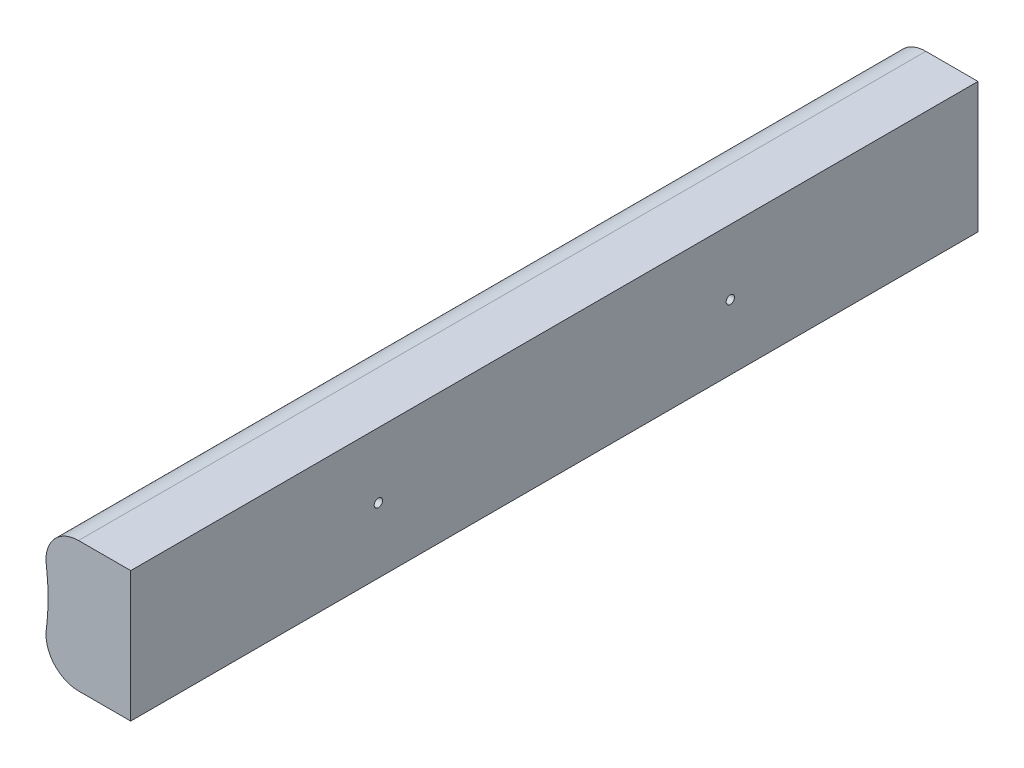
SolidWorks part; units mm, degrees
ref_plane "Front" through (0, 0, 0) normal (0, 0, 1) x (1, 0, 0)
ref_plane "Top" through (0, 0, 0) normal (0, 1, 0) x (1, 0, 0)
ref_plane "Right" through (0, 0, 0) normal (1, 0, 0) x (0, 0, -1)
sketch "Sketch1" plane through (0, 0, 0) normal (0, 0, 1) x (1, 0, 0)
  line L0 (-81.456, -19.8133) -> (-82.3706, -28.3793)
  line L1 (-50.8, -63.5) -> (0, -63.5)
  line L2 (0, -63.5) -> (0, 63.5)
  line L3 (0, 63.5) -> (-50.8, 63.5)
  line L4 (-82.3706, 28.3793) -> (-81.456, 19.8133)
  line L5 (0, 0) -> (-160.6881, 0) construction
  line L6 (-50.8, 96.0303) -> (-50.8, -98.1367) construction
  arc A0 (-82.3706, -28.3793) -> (-50.8, -63.5) centre (-50.8, -31.75) ccw
  arc A1 (-50.8, 63.5) -> (-82.3706, 28.3793) centre (-50.8, 31.75) ccw
  arc A2 (-81.456, -19.8133) -> (-81.456, 19.8133) centre (-267.0315, 0) ccw
  dimension "D2" = 31.75
  dimension "D4" = 186.6302
  dimension "D5" = 50.8
  dimension "D6" = 80.4013
  dimension "D1" = 127
extrude "Extrude1" add sketch "Sketch1" along normal mid plane 825.5
hole_wizard "A (0.234) Diameter Hole1" positions "3DSketch1" profile "Sketch2" hole size "A" standard "Ansi (в дюймах)"
sketch3d "3DSketch1"
  line L1 (0, -63.5, 412.75) -> (0, 63.5, 412.75) construction
  point P0 (0, 0, 171.45)
  point P2 (0, 0, -171.45)
  dimension "D1" = 342.9
  dimension "D2" = 241.3
sketch "Sketch2" plane through (0, 0, 171.45) normal (0, 1, 0) x (0, 0, -1)
  line L0 (0, 0) -> (0, 21.4919)
  line L1 (0, 21.4919) -> (4.064, 19.05)
  line L2 (4.064, 19.05) -> (4.064, 0)
  line L5 (4.064, 0) -> (0, 0)
  line L10 (0, 21.4919) -> (-4.064, 19.05) construction
  line L11 (0, -6.35) -> (0, 107.95) construction
  dimension "Диаметр отверстия" = 8.128
  dimension "Глубина отверстия" = 19.05
  dimension "Угол заточки сверла" = 118
